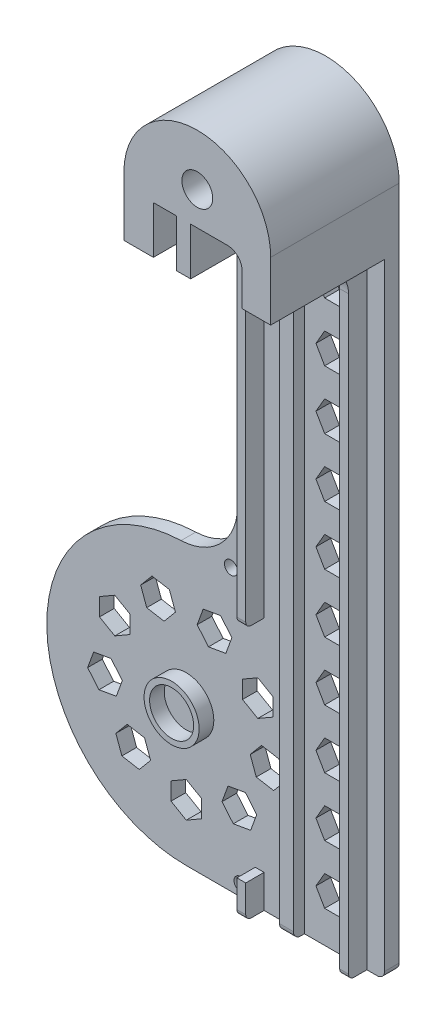
SolidWorks part; units mm, degrees
ref_plane "Ebene vorne" through (0, 0, 0) normal (0, 0, 1) x (1, 0, 0)
ref_plane "Ebene oben" through (0, 0, 0) normal (0, 1, 0) x (1, 0, 0)
ref_plane "Ebene rechts" through (0, 0, 0) normal (1, 0, 0) x (0, 0, -1)
sketch "BodyTop" plane through (0, 0, 0) normal (0, 0, 1) x (1, 0, 0)
  line L0 (0, -19) -> (27, -19)
  line L1 (27, -19) -> (27, 66)
  line L2 (27, 66) -> (7, 66)
  line L3 (7, 66) -> (7, 19)
  line L4 (7, 19) -> (0, 19)
  circle A0 centre (0, 0) radius 19
  dimension "D1" = 38
  dimension "D2" = 27
  dimension "D3" = 20
  dimension "D4" = 85
extrude "body-top" add sketch "BodyTop" along normal mid plane 2 contours A0 | A0 L0 L1 L2 L3 L4
sketch "skizze_lamellen" plane through (0, 0, 1) normal (0, 0, 1) x (1, 0, 0)
  line L0 (27, 66) -> (7, 66) construction
  line L1 (23.4, 66) -> (24.6, 66)
  line L2 (23.4, 66) -> (23.4, -19)
  line L3 (23.4, -19) -> (24.6, -19)
  line L4 (24.6, 66) -> (24.6, -19)
  line L5 (0, -19) -> (27, -19) construction
  line L6 (27, -19) -> (27, 66) construction
  line L7 (9.4, 66) -> (10.6, 66)
  line L8 (9.4, 66) -> (9.4, -19)
  line L9 (9.4, -19) -> (10.6, -19)
  line L10 (10.6, 66) -> (10.6, -19)
  line L11 (7, 66) -> (7, 19) construction
  dimension "D1" = 2.4
  dimension "D2" = 1.2
  dimension "D3" = 2.4
  dimension "D4" = 1.2
extrude "Lammellen" add sketch "skizze_lamellen" along normal blind 2.5
sketch "Skizze1" plane through (0, 0, 1) normal (0, 0, 1) x (1, 0, 0)
  line L0 (23.4, 66) -> (10.6, 66) construction
  line L1 (14.2, 66) -> (16.1, 66)
  line L2 (14.2, 66) -> (14.2, -19)
  line L3 (14.2, -19) -> (16.1, -19)
  line L4 (16.1, 66) -> (16.1, -19)
  line L5 (10.6, -19) -> (23.4, -19) construction
  line L7 (7, 66) -> (7, 19) construction
  dimension "D1" = 1.9
  dimension "D2" = 7.2
extrude "fuehrung" add sketch "Skizze1" along normal blind 1.5
fillet "Verrundung6" radius 1 1 edges at (27, -19, 0)
sketch "sparung" plane through (0, 0, 3.5) normal (0, 0, 1) x (1, 0, 0)
  line L0 (9.4, 66) -> (9.4, -19) construction
  line L1 (9.4, 15.5) -> (10.6, 15.5)
  line L2 (9.4, 15.5) -> (9.4, -14.5)
  line L3 (9.4, -14.5) -> (10.6, -14.5)
  line L4 (10.6, 15.5) -> (10.6, -14.5)
  line L5 (10.6, -19) -> (10.6, 66) construction
  line L6 (9.4, -19) -> (10.6, -19) construction
  dimension "D1" = 30
  dimension "D2" = 4.5
extrude "Aussparung" cut sketch "sparung" against normal blind 2.5
sketch "SkizzeAnbau" plane through (0, 0, 0) normal (0, 0, 1) x (1, 0, 0)
  line L2 (7, 74) -> (7, 66)
  line L3 (7, 66) -> (27, 66)
  line L4 (27, 74) -> (27, 66)
  arc A0 (7, 74) -> (27, 74) centre (17, 74) cw
  dimension "D1" = 8
extrude "Anbauplatte" add sketch "SkizzeAnbau" along normal mid plane 2
sketch "SkizzeStutzen" plane through (0, 0, 1) normal (0, 0, 1) x (1, 0, 0)
  line L0 (7, 74) -> (7, 19) construction
  line L1 (7, 66) -> (27, 66)
  line L2 (7, 66) -> (7, 74)
  line L4 (27, 66) -> (27, 74)
  arc A0 (7, 74) -> (27, 74) centre (17, 74) cw
extrude "anbaustutzen" add sketch "SkizzeStutzen" along normal blind 15.5
sketch "Skizzedruckerzahnrad" plane through (0, 0, 1) normal (0, 0, 1) x (1, 0, 0)
  circle A0 centre (0, 0) radius 3
  circle A1 centre (0, 0) radius 3.75
  dimension "D1" = 7.5
  dimension "D2" = 6
extrude "drucker zahnrad" add sketch "Skizzedruckerzahnrad" along normal blind 2
sketch "SkizzeHalterloch" plane through (0, 0, 16.5) normal (0, 0, 1) x (1, 0, 0)
  line L0 (7, 74) -> (27, 74) construction
  line L1 (17, 84) -> (17, 74) construction
  arc A0 (27, 74) -> (7, 74) centre (17, 74) ccw construction
  circle A2 centre (17, 77) radius 2.1
  dimension "D1" = 4.2
  dimension "D2" = 3
extrude "halterloch" cut sketch "SkizzeHalterloch" against normal blind 18.5
fillet "Verrundung24" radius 8 1 edges at (7, 19, 0)
sketch "Skizzebohrloch" plane through (0, 0, 1) normal (0, 0, 1) x (1, 0, 0)
  line L0 (0, -19) -> (9.4, -19) construction
  line L1 (27, -18) -> (27, 66) construction
  circle A0 centre (7.4, -17.5) radius 0.9
  circle A1 centre (6.1, 19.2) radius 0.9
  dimension "D1" = 1.5
  dimension "D2" = 1.8
  dimension "D4" = 1.8
  dimension "D3" = 19.6
  dimension "D5" = 20.9
  dimension "D6" = 38.2
extrude "bohrloch" cut sketch "Skizzebohrloch" against normal blind 10
sketch "Skizze6" plane through (0, 0, 16.5) normal (0, 0, 1) x (1, 0, 0)
  line L0 (14.2, 66) -> (14.2, -19) construction
  line L1 (16.1, 66) -> (23.1019, 66)
  line L2 (16.1, 66) -> (16.1, 72.4691)
  line L3 (16.1, 72.4691) -> (23.1019, 72.4691)
  line L4 (23.1019, 66) -> (23.1019, 72.4691)
  line L5 (11.0189, 72.4691) -> (14.2, 72.4691)
  line L6 (11.0189, 72.4691) -> (11.0189, 66)
  line L7 (11.0189, 66) -> (14.2, 66)
  line L8 (14.2, 72.4691) -> (14.2, 66)
  line L9 (14.2, 66) -> (14.2, -19) construction
extrude "Schnitt-Linear austragen4" cut sketch "Skizze6" against normal blind 15.5
fillet "Verrundung34" radius 1 1 edges at (15.15, -19, 2.5)
sketch "Skizze7" plane through (0, 0, -1) normal (0, 0, -1) x (-1, 0, 0)
  line L1 (-22.4131, -12.5676) -> (-21.2252, -14.6252)
  line L2 (-21.2252, -14.6252) -> (-18.8493, -14.6252)
  line L3 (-18.8493, -14.6252) -> (-17.6614, -12.5676)
  line L4 (-17.6614, -12.5676) -> (-18.8493, -10.51)
  line L5 (-18.8493, -10.51) -> (-21.2252, -10.51)
  line L6 (-21.2252, -10.51) -> (-22.4131, -12.5676)
  circle A0 centre (-20.0372, -12.5676) radius 2.0576 construction
extrude "Schnitt-Linear austragen5" cut sketch "Skizze7" against normal through all both and the other way through all
pattern_linear "Lineares Muster2" count 11 spacing 8 along (0, 1, 0) of "Schnitt-Linear austragen5"
sketch "Skizze8" plane through (0, 0, 1) normal (0, 0, 1) x (1, 0, 0)
  line L1 (0, -8.8448) -> (-2.0785, -10.0448)
  line L2 (-2.0785, -10.0448) -> (-2.0785, -12.4449)
  line L3 (-2.0785, -12.4449) -> (0, -13.645)
  line L4 (0, -13.645) -> (2.0785, -12.4449)
  line L5 (2.0785, -12.4449) -> (2.0785, -10.0448)
  line L6 (2.0785, -10.0448) -> (0, -8.8448)
  circle A0 centre (0, -11.2449) radius 2.0785 construction
extrude "Schnitt-Linear austragen6" cut sketch "Skizze8" against normal through all both and the other way through all
pattern_circular "Kreismuster1" count 9 over 360 about axis through (0, 0, 0) along (0, 0, 1) of "Schnitt-Linear austragen6"
fillet "Verrundung35" radius 2 1 edges at (23.1019, 72.4691, 8.75)
fillet "Verrundung36" radius 4 1 edges at (10, 66, 3.5)
fillet "Verrundung37" radius 4 1 edges at (24, 66, 3.5)
fillet "Verrundung38" radius 0.75 3 edges at (10, 15.5, 3.5) (10, -19, 3.5) (24, -19, 3.5)
